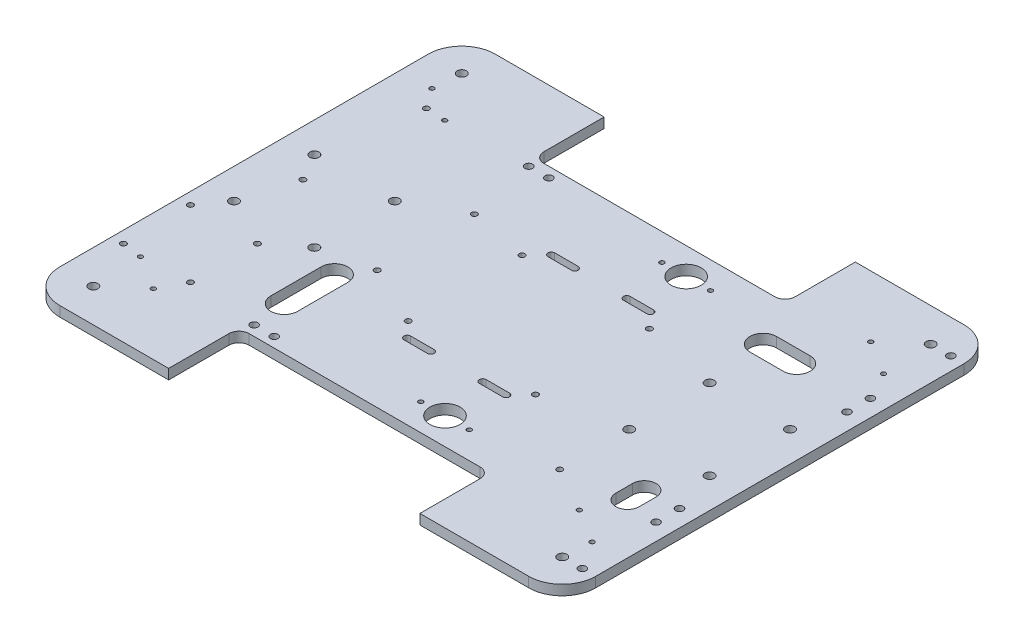
SolidWorks part; units mm, degrees
material "6061-T6 (SS)"
ref_plane "Front Plane" through (0, 0, 0) normal (0, 0, 1) x (1, 0, 0)
ref_plane "Top Plane" through (0, 0, 0) normal (0, 1, 0) x (1, 0, 0)
ref_plane "Right Plane" through (0, 0, 0) normal (1, 0, 0) x (0, 0, -1)
sketch "SK_Outline" plane through (0, 0, 0) normal (0, 1, 0) x (1, 0, 0)
  line L0 (160, -110) -> (160, 110)
  line L1 (140, 130) -> (75, 130)
  line L2 (75, 130) -> (75, 94)
  line L3 (69, 88) -> (-69, 88)
  line L4 (-75, 94) -> (-75, 130)
  line L5 (-75, 130) -> (-140, 130)
  line L6 (-160, 110) -> (-160, -110)
  line L7 (-140, -130) -> (-75, -130)
  line L8 (-75, -130) -> (-75, -94)
  line L9 (-69, -88) -> (69, -88)
  line L10 (75, -94) -> (75, -130)
  line L11 (75, -130) -> (140, -130)
  arc A0 (160, 110) -> (140, 130) centre (140, 110) ccw
  arc A1 (75, 94) -> (69, 88) centre (69, 94) cw
  arc A2 (-69, 88) -> (-75, 94) centre (-69, 94) cw
  arc A3 (-140, 130) -> (-160, 110) centre (-140, 110) ccw
  arc A4 (-160, -110) -> (-140, -130) centre (-140, -110) ccw
  arc A5 (-75, -94) -> (-69, -88) centre (-69, -94) cw
  arc A6 (69, -88) -> (75, -94) centre (69, -94) cw
  arc A7 (140, -130) -> (160, -110) centre (140, -110) ccw
extrude "Plate" add sketch "SK_Outline" along normal blind 6
sketch "SK_DeckPosts_M5" plane through (0, 0, 0) normal (0, 1, 0) x (1, 0, 0)
  circle A0 centre (140, -110) radius 2.75
  circle A1 centre (140, 110) radius 2.75
  circle A2 centre (-140, -110) radius 2.75
  circle A3 centre (-140, 110) radius 2.75
extrude "Cut_DeckPosts_M5" cut sketch "SK_DeckPosts_M5" against normal through all and the other way through all
sketch "SK_CasterMounts_M5" plane through (0, 0, 0) normal (0, 1, 0) x (1, 0, 0)
  circle A0 centre (94, 24) radius 2.75
  circle A1 centre (94, -24) radius 2.75
  circle A2 centre (142, 24) radius 2.75
  circle A3 centre (142, -24) radius 2.75
  circle A4 centre (-142, 24) radius 2.75
  circle A5 centre (-142, -24) radius 2.75
  circle A6 centre (-94, 24) radius 2.75
  circle A7 centre (-94, -24) radius 2.75
extrude "Cut_CasterMounts_M5" cut sketch "SK_CasterMounts_M5" against normal through all and the other way through all
sketch "SK_SpringHoles_18" plane through (0, 0, 0) normal (0, 1, 0) x (1, 0, 0)
  circle A0 centre (32, -72) radius 9
  circle A1 centre (32, 72) radius 9
extrude "Cut_SpringHoles_18" cut sketch "SK_SpringHoles_18" against normal through all and the other way through all
sketch "SK_SpringCups_M2p5" plane through (0, 0, 0) normal (0, 1, 0) x (1, 0, 0)
  circle A0 centre (17.5, -72) radius 1.35
  circle A1 centre (46.5, -72) radius 1.35
  circle A2 centre (17.5, 72) radius 1.35
  circle A3 centre (46.5, 72) radius 1.35
extrude "Cut_SpringCups_M2p5" cut sketch "SK_SpringCups_M2p5" against normal through all and the other way through all
sketch "SK_PivotHangers_M4" plane through (0, 0, 0) normal (0, 1, 0) x (1, 0, 0)
  circle A0 centre (-72, -82) radius 2.25
  circle A1 centre (-60, -82) radius 2.25
  circle A2 centre (-72, 82) radius 2.25
  circle A3 centre (-60, 82) radius 2.25
extrude "Cut_PivotHangers_M4" cut sketch "SK_PivotHangers_M4" against normal through all and the other way through all
sketch "SK_BatteryTray_M3" plane through (0, 0, 0) normal (0, 1, 0) x (1, 0, 0)
  circle A0 centre (-28, -34) radius 1.7
  circle A1 centre (-28, 34) radius 1.7
  circle A2 centre (48, -34) radius 1.7
  circle A3 centre (48, 34) radius 1.7
extrude "Cut_BatteryTray_M3" cut sketch "SK_BatteryTray_M3" against normal through all and the other way through all
sketch "SK_BatteryStraps" plane through (0, 0, 0) normal (0, 1, 0) x (1, 0, 0)
  line L0 (-19.5, -41) -> (-5.5, -41)
  line L1 (-5.5, -45) -> (-19.5, -45)
  line L2 (-19.5, 45) -> (-5.5, 45)
  line L3 (-5.5, 41) -> (-19.5, 41)
  line L4 (25.5, -41) -> (39.5, -41)
  line L5 (39.5, -45) -> (25.5, -45)
  line L6 (25.5, 45) -> (39.5, 45)
  line L7 (39.5, 41) -> (25.5, 41)
  arc A0 (-5.5, -41) -> (-5.5, -45) centre (-5.5, -43) cw
  arc A1 (-19.5, -45) -> (-19.5, -41) centre (-19.5, -43) cw
  arc A2 (-5.5, 45) -> (-5.5, 41) centre (-5.5, 43) cw
  arc A3 (-19.5, 41) -> (-19.5, 45) centre (-19.5, 43) cw
  arc A4 (39.5, -41) -> (39.5, -45) centre (39.5, -43) cw
  arc A5 (25.5, -45) -> (25.5, -41) centre (25.5, -43) cw
  arc A6 (39.5, 45) -> (39.5, 41) centre (39.5, 43) cw
  arc A7 (25.5, 41) -> (25.5, 45) centre (25.5, 43) cw
extrude "Cut_BatteryStraps" cut sketch "SK_BatteryStraps" against normal through all and the other way through all
sketch "SK_PowerBoard_M3" plane through (0, 0, 0) normal (0, 1, 0) x (1, 0, 0)
  circle A0 centre (-132.5, 81.35) radius 1.7
  circle A1 centre (-132.5, 7.65) radius 1.7
extrude "Cut_PowerBoard_M3" cut sketch "SK_PowerBoard_M3" against normal through all and the other way through all
sketch "SK_MotorDriver_M3" plane through (0, 0, 0) normal (0, 1, 0) x (1, 0, 0)
  circle A0 centre (-153, -39) radius 1.7
  circle A1 centre (-153, -79) radius 1.7
  circle A2 centre (-113, -39) radius 1.7
  circle A3 centre (-113, -79) radius 1.7
extrude "Cut_MotorDriver_M3" cut sketch "SK_MotorDriver_M3" against normal through all and the other way through all
sketch "SK_Splices_M3" plane through (0, 0, 0) normal (0, 1, 0) x (1, 0, 0)
  circle A0 centre (-63.5, 41) radius 1.7
  circle A1 centre (-63.5, -17) radius 1.7
extrude "Cut_Splices_M3" cut sketch "SK_Splices_M3" against normal through all and the other way through all
sketch "SK_ChargeContacts_M4" plane through (0, 0, 0) normal (0, 1, 0) x (1, 0, 0)
  circle A0 centre (150, -50) radius 2.25
  circle A1 centre (150, -64) radius 2.25
  circle A2 centre (150, 50) radius 2.25
  circle A3 centre (150, 64) radius 2.25
extrude "Cut_ChargeContacts_M4" cut sketch "SK_ChargeContacts_M4" against normal through all and the other way through all
sketch "SK_Bumper_M4" plane through (0, 0, 0) normal (0, 1, 0) x (1, 0, 0)
  circle A0 centre (152, -110) radius 2.25
  circle A1 centre (152, 110) radius 2.25
extrude "Cut_Bumper_M4" cut sketch "SK_Bumper_M4" against normal through all and the other way through all
sketch "SK_CliffSensors_M2p5" plane through (0, 0, 0) normal (0, 1, 0) x (1, 0, 0)
  circle A0 centre (120.84, -80.65) radius 1.35
  circle A1 centre (141.16, -93.35) radius 1.35
  circle A2 centre (120.84, 93.35) radius 1.35
  circle A3 centre (141.16, 80.65) radius 1.35
  circle A4 centre (-141.16, -80.65) radius 1.35
  circle A5 centre (-120.84, -93.35) radius 1.35
  circle A6 centre (-141.16, 93.35) radius 1.35
  circle A7 centre (-120.84, 80.65) radius 1.35
extrude "Cut_CliffSensors_M2p5" cut sketch "SK_CliffSensors_M2p5" against normal through all and the other way through all
sketch "SK_FuseF2_M3" plane through (0, 0, 0) normal (0, 1, 0) x (1, 0, 0)
  circle A0 centre (94, -65.5) radius 1.7
extrude "Cut_FuseF2_M3" cut sketch "SK_FuseF2_M3" against normal through all and the other way through all
sketch "SK_PassThroughs" plane through (0, 0, 0) normal (0, 1, 0) x (1, 0, 0)
  line L0 (-66, -32) -> (-66, -62)
  line L1 (-82, -62) -> (-82, -32)
  line L2 (90, 68) -> (110, 68)
  line L3 (110, 52) -> (90, 52)
  line L4 (137, -51) -> (137, -61)
  line L5 (123, -61) -> (123, -51)
  arc A0 (-66, -62) -> (-82, -62) centre (-74, -62) cw
  arc A1 (-82, -32) -> (-66, -32) centre (-74, -32) cw
  arc A2 (110, 68) -> (110, 52) centre (110, 60) cw
  arc A3 (90, 52) -> (90, 68) centre (90, 60) cw
  arc A4 (137, -61) -> (123, -61) centre (130, -61) cw
  arc A5 (123, -51) -> (137, -51) centre (130, -51) cw
extrude "Cut_PassThroughs" cut sketch "SK_PassThroughs" against normal through all and the other way through all
